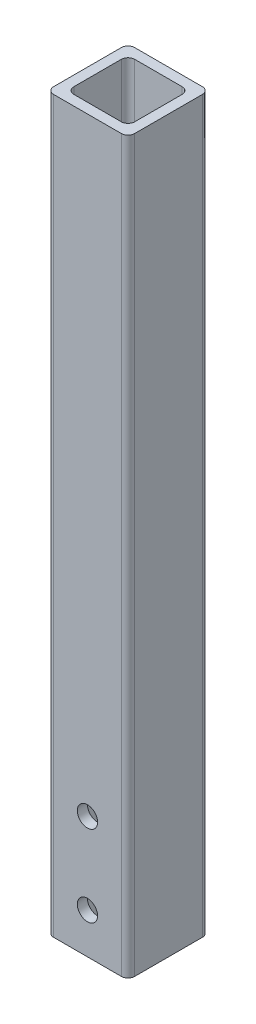
SolidWorks part; units mm, degrees
material "6061-T6 (SS)"
ref_plane "Front Plane" through (0, 0, 0) normal (0, 0, 1) x (1, 0, 0)
ref_plane "Top Plane" through (0, 0, 0) normal (0, 1, 0) x (1, 0, 0)
ref_plane "Right Plane" through (0, 0, 0) normal (1, 0, 0) x (0, 0, -1)
sketch "Sketch1" plane through (0, 0, 0) normal (0, 1, 0) x (1, 0, 0)
  line L0 (9.525, 9.525) -> (-9.525, 9.525)
  line L1 (12.7, -12.7) -> (-12.7, -12.7)
  line L2 (12.7, -12.7) -> (12.7, 12.7)
  line L3 (12.7, 12.7) -> (-12.7, 12.7)
  line L4 (-12.7, -12.7) -> (-12.7, 12.7)
  line L5 (12.7, -12.7) -> (-12.7, 12.7) construction
  line L6 (12.7, 12.7) -> (-12.7, -12.7) construction
  line L7 (-9.525, -9.525) -> (-9.525, 9.525)
  line L8 (9.525, -9.525) -> (-9.525, -9.525)
  line L9 (9.525, -9.525) -> (9.525, 9.525)
  point P0 (0, 0)
  dimension "D1" = 25.4
  dimension "D2" = 25.4
  dimension "D3" = 3.175
extrude "Boss-Extrude1" add sketch "Sketch1" along normal blind 1219.2
fillet "Fillet1" radius 2.1082 8 edges at (9.525, 609.6, -9.525) (-9.525, 609.6, -9.525) (-9.525, 609.6, 9.525) (9.525, 609.6, 9.525) (12.7, 609.6, -12.7) (-12.7, 609.6, -12.7) (-12.7, 609.6, 12.7) (12.7, 609.6, 12.7)
sketch "Sketch2" plane through (12.7, 0, 0) normal (1, 0, 0) x (0, 0, -1)
  line L1 (-38.375, 0) -> (123.0295, 0)
  line L2 (-38.375, 0) -> (-38.375, 228.6)
  line L3 (-38.375, 228.6) -> (123.0295, 228.6)
  line L4 (123.0295, 0) -> (123.0295, 228.6)
  dimension "D1" = 228.6
extrude "Cut-Extrude1" cut sketch "Sketch2" against normal through all flip side to cut
sketch "Sketch5" plane through (0, 0, 12.7) normal (0, 0, 1) x (1, 0, 0)
  line L0 (-10.5918, 0) -> (10.5918, 0) construction
  circle A0 centre (0, 12.7) radius 3.175
  circle A1 centre (0, 38.1) radius 3.175
  point P0 (0, 0)
  dimension "D1" = 6.35
  dimension "D3" = 6.35
  dimension "D2" = 12.7
  dimension "D4" = 38.1
extrude "Cut-Extrude3" cut sketch "Sketch5" against normal through all both and the other way through all
